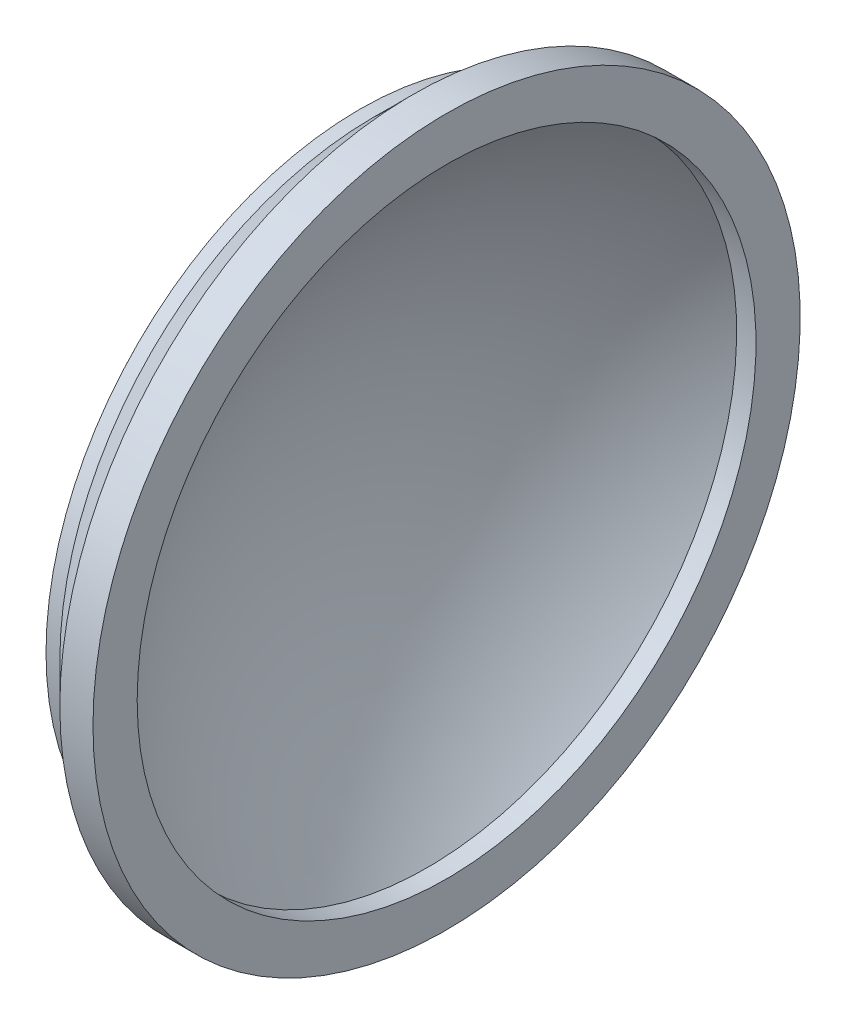
SolidWorks part; units mm, degrees
ref_plane "Front Plane" through (0, 0, 0) normal (0, 0, 1) x (1, 0, 0)
ref_plane "Top Plane" through (0, 0, 0) normal (0, 1, 0) x (1, 0, 0)
ref_plane "Right Plane" through (0, 0, 0) normal (1, 0, 0) x (0, 0, -1)
sketch "Sketch1" plane through (0, 0, 0) normal (0, 0, 1) x (1, 0, 0)
  line L0 (-128.5458, 0) -> (99.0674, 0) construction
  line L1 (-31.7204, 56.7796) -> (-29.2204, 56.7796)
  line L2 (-29.2204, 56.7796) -> (-22, 64)
  line L3 (-22, 64) -> (-16, 64)
  line L4 (-16, 64) -> (-16, 56)
  line L5 (-16, 56) -> (-19.5009, 56)
  line L6 (-50.5556, 0) -> (-40.5556, 0)
  arc A0 (-19.5009, 56) -> (-40.5556, 0) centre (44.4444, 0) ccw
  arc A1 (-31.7204, 56.7796) -> (-50.5556, 0) centre (44.4444, 0) ccw
  point P11 (0, 0)
  point P13 (0, 0)
  point P14 (0, 0)
  dimension "D3" = 95
  dimension "D4" = 85
  dimension "D1" = 64
  dimension "D2" = 16
  dimension "D5" = 6
  dimension "D6" = 8
  dimension "D7" = 2.5
  dimension "D8" = 135
revolve "Revolve1" add sketch "Sketch1" angle 360 about L0
